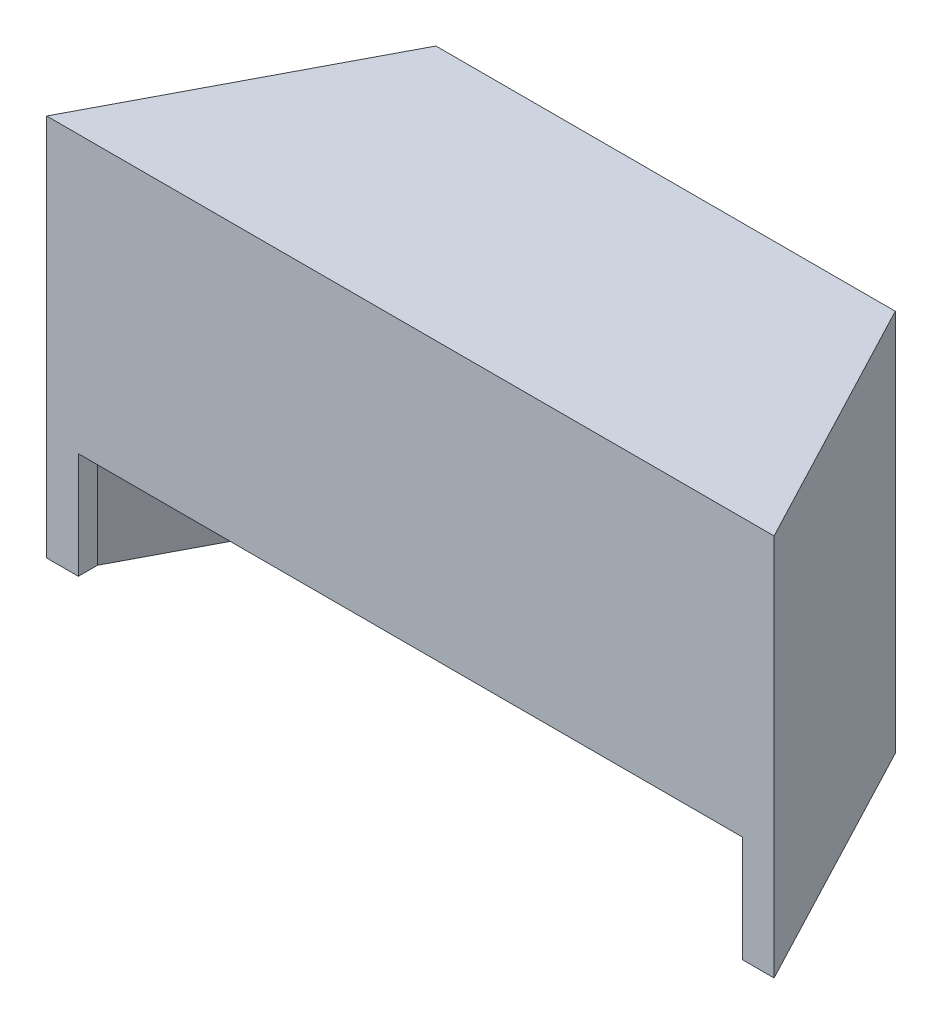
SolidWorks part; units mm, degrees
ref_plane "Alzado" through (0, 0, 0) normal (0, 0, 1) x (1, 0, 0)
ref_plane "Planta" through (0, 0, 0) normal (0, 1, 0) x (1, 0, 0)
ref_plane "Vista lateral" through (0, 0, 0) normal (1, 0, 0) x (0, 0, -1)
sketch "Croquis1" plane through (0, 0, 0) normal (0, 1, 0) x (1, 0, 0)
  line L0 (-28.5, -0.2059) -> (-18, 19.7941)
  line L1 (0, -55) -> (0, 55) construction
  line L2 (18, 19.7941) -> (28.5, -0.2059)
  line L4 (-18, 19.7941) -> (18, 19.7941)
  line L5 (-28.5, -0.2059) -> (28.5, -0.2059)
  dimension "D1" = 57
  dimension "D2" = 28.5
  dimension "D3" = 18
  dimension "D4" = 36
  dimension "D5" = 20
extrude "Saliente-Extruir1" add sketch "Croquis1" along normal blind 30
shell "Vaciado1" thickness 1.5
sketch "Croquis3" plane through (0, 0, -19.7941) normal (0, 0, -1) x (-1, 0, 0)
  line L1 (-5, -20) -> (5, -20)
  line L2 (-5, -20) -> (-5, 20)
  line L3 (-5, 20) -> (5, 20)
  line L4 (5, -20) -> (5, 20)
  line L5 (-5, -20) -> (5, 20) construction
  line L6 (-5, 20) -> (5, -20) construction
  point P0 (0, 0)
  dimension "D1" = 10
  dimension "D2" = 40
extrude "Cortar-Extruir1" [suppressed] cut sketch "Croquis3" against normal blind 22
sketch "Croquis4" plane through (0, 0, -19.7941) normal (0, 0, -1) x (-1, 0, 0)
  line L0 (11, 0) -> (-11, 0) construction
  line L1 (-18, 0) -> (18, 0)
  line L2 (-18, 0) -> (-18, 8.3)
  line L3 (-18, 8.3) -> (18, 8.3)
  line L4 (18, 0) -> (18, 8.3)
  line L5 (-18, 30) -> (-18, 0) construction
  line L6 (18, 30) -> (18, 0) construction
  dimension "D1" = 8.3
extrude "Cortar-Extruir2" cut sketch "Croquis4" against normal blind 10
sketch "Croquis5" plane through (0, 0, -1.2941) normal (0, 0, -1) x (-1, 0, 0)
  line L0 (11, 0) -> (-11, 0) construction
  line L1 (-26.0183, 0) -> (26.0183, 0)
  line L2 (-26.0183, 0) -> (-26.0183, 8.3229)
  line L3 (-26.0183, 8.3229) -> (26.0183, 8.3229)
  line L4 (26.0183, 0) -> (26.0183, 8.3229)
  line L5 (-26.0183, 28.5) -> (-26.0183, 0) construction
  line L6 (26.0183, 28.5) -> (26.0183, 0) construction
extrude "Cortar-Extruir3" cut sketch "Croquis5" against normal blind 10
